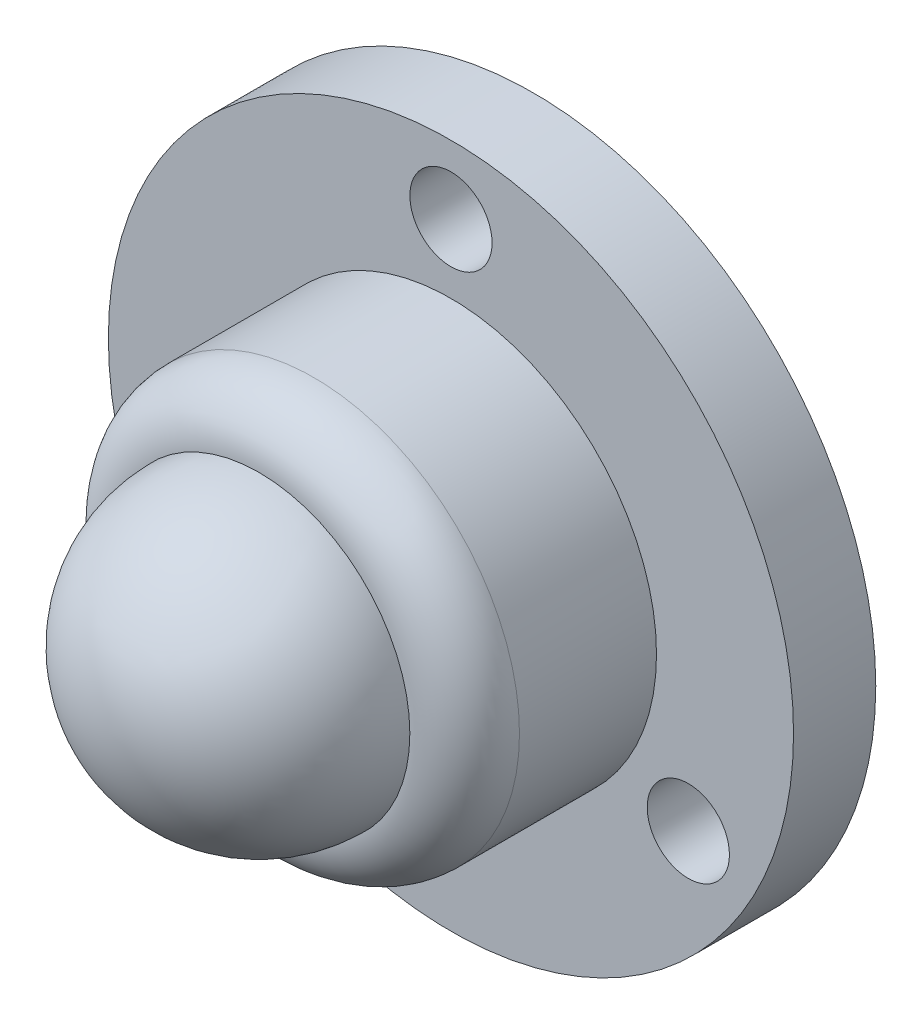
SolidWorks part; units mm, degrees
ref_plane "Front Plane" through (0, 0, 0) normal (0, 0, 1) x (1, 0, 0)
ref_plane "Top Plane" through (0, 0, 0) normal (0, 1, 0) x (1, 0, 0)
ref_plane "Right Plane" through (0, 0, 0) normal (1, 0, 0) x (0, 0, -1)
sketch "Sketch2" plane through (0, 0, 0) normal (0, 0, 1) x (1, 0, 0)
  circle A0 centre (0, 0) radius 1.25
  circle A2 centre (0, 1) radius 0.15
  circle A3 centre (0.866, -0.5) radius 0.15
  circle A4 centre (-0.866, -0.5) radius 0.15
  point P12 (0, 0)
  dimension "D1" = 2.5
  dimension "D3" = 0.3
  dimension "D4" = 3
extrude "Boss-Extrude1" add sketch "Sketch2" along normal blind 0.3
sketch "Sketch3" plane through (0, 0, 0.3) normal (0, 0, 1) x (1, 0, 0)
  circle A1 centre (0, 0) radius 0.75
extrude "Boss-Extrude2" add sketch "Sketch3" along normal blind 0.7
fillet "Fillet2" radius 0.2 1 edges at (0.75, 0, 1)
sketch "Sketch5" plane through (0, 0, 1) normal (0, 0, 1) x (1, 0, 0)
  line L0 (-0.55, 0) -> (0.55, 0)
  circle A0 centre (0, 0) radius 0.55 construction
  arc A1 (0.55, 0) -> (-0.55, 0) centre (0, 0) ccw
revolve "Revolve2" add sketch "Sketch5" angle 360 about L0
